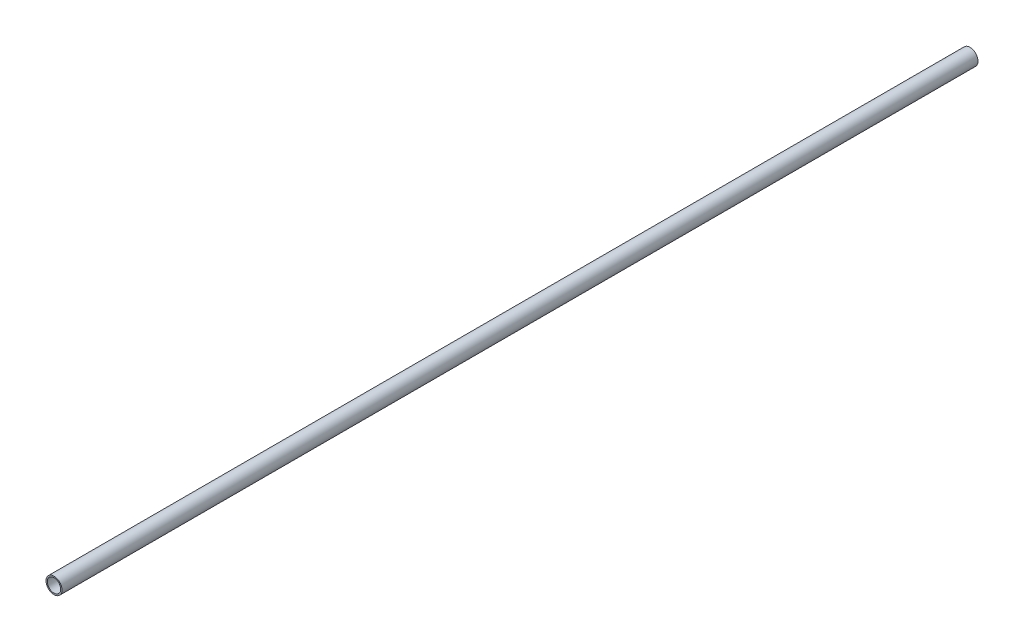
SolidWorks part; units mm, degrees
ref_plane "前视基准面" through (0, 0, 0) normal (0, 0, 1) x (1, 0, 0)
ref_plane "上视基准面" through (0, 0, 0) normal (0, 1, 0) x (1, 0, 0)
ref_plane "右视基准面" through (0, 0, 0) normal (1, 0, 0) x (0, 0, -1)
other "Configuration Table"
sketch "草图1" plane through (0, 0, 0) normal (0, 0, 1) x (1, 0, 0)
  circle A0 centre (0, 0) radius 5
  dimension "D1" = 10
extrude "拉伸-薄壁1" add sketch "草图1" along normal blind 685 thin
